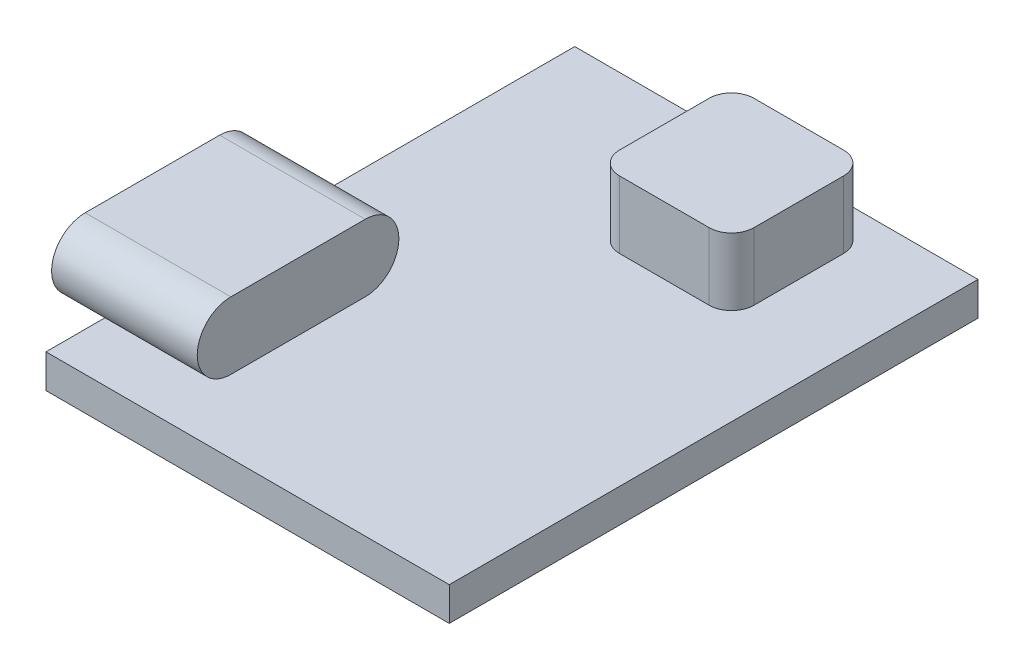
SolidWorks part; units mm, degrees
material "ABS"
ref_plane "Front Plane" through (0, 0, 0) normal (0, 0, 1) x (1, 0, 0)
ref_plane "Top Plane" through (0, 0, 0) normal (0, 1, 0) x (1, 0, 0)
ref_plane "Right Plane" through (0, 0, 0) normal (1, 0, 0) x (0, 0, -1)
sketch "Sketch1" plane through (0, 0, 0) normal (0, 1, 0) x (1, 0, 0)
  line L1 (-9, 11.8) -> (9, 11.8)
  line L2 (-9, 11.8) -> (-9, -11.8)
  line L3 (-9, -11.8) -> (9, -11.8)
  line L4 (9, 11.8) -> (9, -11.8)
  line L5 (0, -11.8) -> (0, 11.8) construction
  line L6 (-9, 0) -> (9, 0) construction
  point P0 (0, 0)
  dimension "D1" = 18
  dimension "D2" = 23.6
extrude "Boss-Extrude1" add sketch "Sketch1" along normal blind 1.5
sketch "Sketch3" plane through (-9, 0, 0) normal (-1, 0, 0) x (0, 0, 1)
  line L0 (2.55, 3) -> (8.55, 3) construction
  line L1 (2.55, 4.5) -> (8.55, 4.5)
  line L2 (2.55, 1.5) -> (8.55, 1.5)
  line L3 (-11.8, 1.5) -> (11.8, 1.5) construction
  line L4 (11.8, 1.5) -> (11.8, 0) construction
  arc A0 (2.55, 4.5) -> (2.55, 1.5) centre (2.55, 3) ccw
  arc A1 (8.55, 1.5) -> (8.55, 4.5) centre (8.55, 3) ccw
  point P2 (5.55, 3)
  point P7 (1.05, 3)
  point P8 (10.05, 3)
  dimension "D1" = 9
  dimension "D2" = 3
  dimension "D3" = 6.25
extrude "Boss-Extrude2" add sketch "Sketch3" along normal blind 1.5 and the other way blind 5 separate body
shell "Shell1" thickness 0.3
sketch "Sketch4" plane through (0, 1.5, 0) normal (0, 1, 0) x (1, 0, 0)
  line L0 (9, 11.8) -> (-9, 11.8) construction
  line L1 (-1, 10.8) -> (5, 10.8)
  line L2 (-1, 10.8) -> (-1, 4.8)
  line L3 (-1, 4.8) -> (5, 4.8)
  line L4 (5, 10.8) -> (5, 4.8)
  line L5 (9, -11.8) -> (9, 11.8) construction
  dimension "D1" = 6
  dimension "D2" = 1
  dimension "D3" = 4
extrude "Boss-Extrude3" add sketch "Sketch4" along normal blind 3 separate body
fillet "Fillet1" radius 1 4 edges at (5, 3, -10.8) (-1, 3, -10.8) (-1, 3, -4.8) (5, 3, -4.8)
